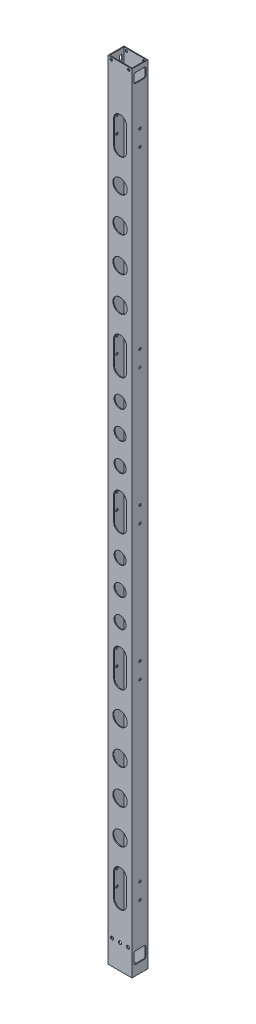
SolidWorks part; units mm, degrees
material "6061 合金"
ref_plane "Front" through (0, 0, 0) normal (0, 0, 1) x (1, 0, 0)
ref_plane "Top" through (0, 0, 0) normal (0, 1, 0) x (1, 0, 0)
ref_plane "Right" through (0, 0, 0) normal (1, 0, 0) x (0, 0, -1)
sketch "草图1" plane through (0, 0, 0) normal (0, 1, 0) x (1, 0, 0)
  line L1 (-15, -10) -> (15, -10)
  line L2 (-15, -10) -> (-15, 10)
  line L3 (-15, 10) -> (15, 10)
  line L4 (15, -10) -> (15, 10)
  line L5 (-15, -10) -> (15, 10) construction
  line L6 (-15, 10) -> (15, -10) construction
  line L7 (-14, -9) -> (14, -9)
  line L8 (-14, -9) -> (-14, 9)
  line L9 (-14, 9) -> (14, 9)
  line L10 (14, -9) -> (14, 9)
  line L11 (-14, -9) -> (14, 9) construction
  line L12 (-14, 9) -> (14, -9) construction
  point P0 (0, 0)
  point P5 (0, 0)
  dimension "D1" = 20
  dimension "D2" = 30
  dimension "D3" = 1
  dimension "D4" = 1
extrude "凸台-拉伸1" add sketch "草图1" along normal blind 980
sketch "草图3" plane through (15, 0, 0) normal (1, 0, 0) x (0, 0, -1)
  line L0 (0, 310) -> (0, 330) construction
  line L1 (0, 0) -> (0, 50000) construction
  line L2 (0, 910) -> (0, 890) construction
  line L4 (-10, 980) -> (10, 980) construction
  line L5 (-10, 490) -> (10, 490) construction
  line L6 (-10, 980) -> (-10, 0) construction
  line L7 (10, 980) -> (10, 0) construction
  line L8 (0, 500) -> (0, 480) construction
  line L9 (0, 670) -> (0, 650) construction
  line L10 (0, 70) -> (0, 90) construction
  circle A4 centre (0, 890) radius 1.5
  circle A5 centre (0, 910) radius 1.5
  circle A10 centre (0, 500) radius 1.5
  circle A11 centre (0, 480) radius 1.5
  circle A12 centre (0, 670) radius 1.5
  circle A13 centre (0, 650) radius 1.5
  circle A14 centre (0, 330) radius 1.5
  circle A15 centre (0, 310) radius 1.5
  circle A16 centre (0, 70) radius 1.5
  circle A17 centre (0, 90) radius 1.5
  dimension "D6" = 3
  dimension "D8" = 3
  dimension "D9" = 3
  dimension "D12" = 70
  dimension "D15" = 20
  dimension "D16" = 3
  dimension "D7" = 3
  dimension "D11" = 10
  dimension "D14" = 3
  dimension "D10" = 20
  dimension "D13" = 20
  dimension "D17" = 220
extrude "切除-拉伸2" cut sketch "草图3" against normal through all
sketch "草图4" plane through (15, 0, 0) normal (1, 0, 0) x (0, 0, -1)
  line L0 (0, 0) -> (0, 50000) construction
  line L1 (-10, 0) -> (10, 0) construction
  line L2 (-10, 980) -> (10, 980) construction
  line L3 (5, 968) -> (5, 972) construction
  line L4 (3.4, 968) -> (3.4, 972)
  line L5 (6.6, 968) -> (6.6, 972)
  line L6 (-5, 968) -> (-5, 972) construction
  line L7 (-3.4, 968) -> (-3.4, 972)
  line L8 (-6.6, 968) -> (-6.6, 972)
  circle A0 centre (-5, 10) radius 1.6 construction
  circle A1 centre (5, 10) radius 1.6 construction
  circle A2 centre (-5, 970) radius 1.6 construction
  circle A3 centre (5, 970) radius 1.6 construction
  arc A4 (3.4, 968) -> (6.6, 968) centre (5, 968) ccw
  arc A5 (6.6, 972) -> (3.4, 972) centre (5, 972) ccw
  arc A6 (-3.4, 968) -> (-6.6, 968) centre (-5, 968) cw
  arc A7 (-6.6, 972) -> (-3.4, 972) centre (-5, 972) cw
  point P17 (5, 970)
  point P24 (-5, 970)
  dimension "D1" = 3.2
  dimension "D4" = 3.2
  dimension "D7" = 1.6
  dimension "D2" = 10
  dimension "D3" = 10
  dimension "D5" = 10
  dimension "D6" = 10
  dimension "D8" = 4
extrude "切除-拉伸3" cut sketch "草图4" against normal through all
sketch "草图5" plane through (15, 0, 0) normal (1, 0, 0) x (0, 0, -1)
  line L0 (0, 0) -> (0, 50000) construction
  line L1 (10, 968) -> (-10, 968) construction
  line L2 (10, 980) -> (10, 0) construction
  line L3 (-10, 980) -> (-10, 0) construction
  line L4 (-10, 980) -> (10, 980) construction
  line L6 (-7.5, 974) -> (7.5, 974)
  line L7 (-7.5, 974) -> (-7.5, 962)
  line L8 (-7.5, 962) -> (7.5, 962)
  line L9 (7.5, 974) -> (7.5, 962)
  line L10 (-7.5, 974) -> (7.5, 962) construction
  line L11 (-7.5, 962) -> (7.5, 974) construction
  point P13 (0, 968)
  point P18 (0, 970)
  dimension "D1" = 12
  dimension "D2" = 12
  dimension "D3" = 15
extrude "切除-拉伸4" cut sketch "草图5" against normal blind 10
sketch "草图6" plane through (0, 0, -10) normal (0, 0, -1) x (-1, 0, 0)
  line L0 (-15, 91.5) -> (-15, 88.5) construction
  line L1 (-15, 71.5) -> (-15, 68.5) construction
  line L2 (-15, 91.5) -> (-15, 88.5) construction
  line L3 (-15, 71.5) -> (-15, 68.5) construction
  line L4 (-15, 891.5) -> (-15, 888.5) construction
  line L5 (-15, 911.5) -> (-15, 908.5) construction
  line L6 (-15, 671.5) -> (-15, 668.5) construction
  line L7 (-15, 651.5) -> (-15, 648.5) construction
  line L8 (-15, 501.5) -> (-15, 498.5) construction
  line L9 (-15, 481.5) -> (-15, 478.5) construction
  line L10 (-15, 331.5) -> (-15, 328.5) construction
  line L11 (-15, 311.5) -> (-15, 308.5) construction
  line L12 (-15, 891.5) -> (-15, 888.5) construction
  line L13 (-15, 911.5) -> (-15, 908.5) construction
  line L14 (-15, 671.5) -> (-15, 668.5) construction
  line L15 (-15, 651.5) -> (-15, 648.5) construction
  line L16 (-15, 501.5) -> (-15, 498.5) construction
  line L17 (-15, 481.5) -> (-15, 478.5) construction
  line L18 (-15, 331.5) -> (-15, 328.5) construction
  line L19 (-15, 311.5) -> (-15, 308.5) construction
  line L20 (0, 65) -> (0, 95) construction
  line L21 (-8, 65) -> (-8, 95)
  line L22 (8, 65) -> (8, 95)
  line L23 (0, 475) -> (0, 505) construction
  line L24 (-15, 88.5) -> (-15, 71.5) construction
  line L25 (-15, 80) -> (-40.807, 80) construction
  line L26 (0, 305) -> (0, 335) construction
  line L27 (-8, 305) -> (-8, 335)
  line L28 (8, 305) -> (8, 335)
  line L29 (0, 65) -> (0, 305) construction
  line L30 (-8, 475) -> (-8, 505)
  line L31 (8, 475) -> (8, 505)
  line L32 (0, 645) -> (0, 675) construction
  line L33 (-8, 645) -> (-8, 675)
  line L34 (8, 645) -> (8, 675)
  line L35 (0, 305) -> (0, 475) construction
  line L36 (0, 885) -> (0, 915) construction
  line L37 (-8, 885) -> (-8, 915)
  line L38 (8, 885) -> (8, 915)
  line L39 (0, 645) -> (0, 885) construction
  line L40 (0, 490) -> (-90.401, 490) construction
  arc A0 (-8, 65) -> (8, 65) centre (0, 65) ccw
  arc A1 (8, 95) -> (-8, 95) centre (0, 95) ccw
  arc A2 (-8, 305) -> (8, 305) centre (0, 305) ccw
  arc A3 (8, 335) -> (-8, 335) centre (0, 335) ccw
  arc A4 (-8, 475) -> (8, 475) centre (0, 475) ccw
  arc A5 (8, 505) -> (-8, 505) centre (0, 505) ccw
  arc A6 (-8, 645) -> (8, 645) centre (0, 645) ccw
  arc A7 (8, 675) -> (-8, 675) centre (0, 675) ccw
  arc A8 (-8, 885) -> (8, 885) centre (0, 885) ccw
  arc A9 (8, 915) -> (-8, 915) centre (0, 915) ccw
  circle A10 centre (0, 135) radius 9
  circle A11 centre (0, 178.3333) radius 9
  circle A12 centre (0, 221.6667) radius 9
  circle A13 centre (0, 265) radius 9
  circle A14 centre (0, 845) radius 9
  circle A16 centre (0, 801.6667) radius 9
  circle A17 centre (0, 758.3333) radius 9
  circle A18 centre (0, 715) radius 9
  circle A19 centre (0, 440) radius 7.5
  circle A20 centre (0, 405) radius 7.5
  circle A21 centre (0, 370) radius 7.5
  circle A22 centre (0, 610) radius 7.5
  circle A23 centre (0, 575) radius 7.5
  circle A24 centre (0, 540) radius 7.5
  point P23 (0, 80)
  point P34 (0, 320)
  point P42 (0, 490)
  point P49 (0, 660)
  point P58 (0, 900)
  dimension "D1" = 8
  dimension "D10" = 18
  dimension "D11" = 40
  dimension "D12" = 40
  dimension "D13" = 43.3333
  dimension "D14" = 40
  dimension "D16" = 40
  dimension "D18" = 35
  dimension "D19" = 35
  dimension "D20" = 35
  dimension "D21" = 15
  dimension "D2" = 30
  dimension "D3" = 2
  dimension "D4" = 240
  dimension "D5" = 3
  dimension "D6" = 170
  dimension "D8" = 240
  dimension "D9" = 4
  dimension "D7" = 2
  dimension "D15" = 4
  dimension "D17" = 3
extrude "切除-拉伸5" cut sketch "草图6" against normal through all
sketch "草图7" plane through (15, 0, 0) normal (1, 0, 0) x (0, 0, -1)
  line L1 (-10, 980) -> (-10, 0) construction
  line L2 (-10, 0) -> (10, 0) construction
  line L3 (0, 0) -> (0, 24.669) construction
  line L4 (-10, 980) -> (10, 980) construction
  circle A0 centre (-5, 5) radius 1.5
  circle A1 centre (5, 5) radius 1.5
  circle A2 centre (-5, 975) radius 1.5
  circle A3 centre (5, 975) radius 1.5
  dimension "D1" = 5
  dimension "D2" = 5
  dimension "D3" = 3
  dimension "D4" = 5
  dimension "D5" = 5
  dimension "D6" = 3
extrude "切除-拉伸6" [suppressed] cut sketch "草图7" against normal through all
sketch "草图9" plane through (0, 0, 10) normal (0, 0, 1) x (1, 0, 0)
  line L0 (15, 980) -> (15, 0) construction
  line L1 (-15, 0) -> (15, 0) construction
  line L2 (0, 0) -> (0, 1062.0992) construction
  line L3 (-15, 980) -> (15, 980) construction
  circle A0 centre (11, 3) radius 1.5 construction
  circle A1 centre (11, 977) radius 1.5
  circle A2 centre (-11, 3) radius 1.5 construction
  circle A3 centre (-11, 977) radius 1.5
  dimension "D3" = 3
  dimension "D4" = 4
  dimension "D5" = 3
  dimension "D1" = 4
  dimension "D2" = 3
extrude "切除-拉伸7" cut sketch "草图9" against normal through all
sketch "草图13" plane through (0, 0, 0) normal (0, -1, 0) x (1, 0, 0)
  line L4 (15, -10) -> (15, 10)
  line L5 (15, 10) -> (-15, 10)
  line L6 (-15, 10) -> (-15, -10)
  line L7 (-15, -10) -> (15, -10)
  line L8 (15, -10) -> (15, 10)
  line L9 (15, 10) -> (-15, 10)
  line L10 (-15, 10) -> (-15, -10)
  line L11 (-15, -10) -> (15, -10)
  line L12 (14, 9) -> (-14, 9)
  line L13 (14, -9) -> (14, 9)
  line L14 (-14, -9) -> (14, -9)
  line L15 (-14, 9) -> (-14, -9)
  line L16 (14, 9) -> (-14, 9)
  line L17 (14, -9) -> (14, 9)
  line L18 (-14, -9) -> (14, -9)
  line L19 (-14, 9) -> (-14, -9)
  dimension "D1" = 0
  dimension "D2" = 0
extrude "凸台-拉伸2" add sketch "草图13" along normal blind 10
sketch "草图11" plane through (-14, 0, 0) normal (1, 0, 0) x (0, 0, -1)
  line L0 (0, 0) -> (0, 111.3677) construction
  line L1 (-5, 5) -> (-5, 15) construction
  line L2 (-6.6, 5) -> (-6.6, 15)
  line L3 (-3.4, 5) -> (-3.4, 15)
  line L4 (5, 5) -> (5, 15) construction
  line L5 (6.6, 5) -> (6.6, 15)
  line L6 (3.4, 5) -> (3.4, 15)
  line L8 (10, -10) -> (-10, -10) construction
  arc A0 (-6.6, 5) -> (-3.4, 5) centre (-5, 5) ccw
  arc A1 (-3.4, 15) -> (-6.6, 15) centre (-5, 15) ccw
  arc A2 (6.6, 5) -> (3.4, 5) centre (5, 5) cw
  arc A3 (3.4, 15) -> (6.6, 15) centre (5, 15) cw
  point P5 (-5, 10)
  point P12 (5, 10)
  dimension "D4" = 1.6
  dimension "D1" = 10
  dimension "D2" = 20
  dimension "D3" = 10
extrude "切除-拉伸8" cut sketch "草图11" against normal blind 60
sketch "草图15" plane through (15, 0, 0) normal (1, 0, 0) x (0, 0, -1)
  line L0 (0, -10) -> (0, 26.437) construction
  line L1 (10, -10) -> (-10, -10) construction
  line L3 (-7.5, 17.5) -> (7.5, 17.5)
  line L4 (-7.5, 17.5) -> (-7.5, 2.5)
  line L5 (-7.5, 2.5) -> (7.5, 2.5)
  line L6 (7.5, 17.5) -> (7.5, 2.5)
  line L7 (-7.5, 17.5) -> (7.5, 2.5) construction
  line L8 (-7.5, 2.5) -> (7.5, 17.5) construction
  point P5 (0, 10)
  dimension "D1" = 20
  dimension "D2" = 15
  dimension "D3" = 15
extrude "切除-拉伸10" cut sketch "草图15" against normal blind 5
fillet "圆角1" radius 2 4 edges at (14.5, 2.5, -7.5) (14.5, 2.5, 7.5) (14.5, 17.5, -7.5) (14.5, 17.5, 7.5)
sketch "草图16" plane through (0, 0, 10) normal (0, 0, 1) x (1, 0, 0)
  line L0 (0, -10) -> (0, 90.7842) construction
  line L1 (15, -10) -> (-15, -10) construction
  circle A0 centre (10, 21) radius 2
  circle A1 centre (0, 21) radius 2
  circle A2 centre (-10, 21) radius 2
  point P11 (8.9428, 14.8541)
  dimension "D1" = 31
  dimension "D2" = 4
  dimension "D3" = 20
extrude "切除-拉伸11" cut sketch "草图16" against normal blind 90
fillet "圆角2" radius 2 4 edges at (14.5, 962, -7.5) (14.5, 962, 7.5) (14.5, 974, 7.5) (14.5, 974, -7.5)
